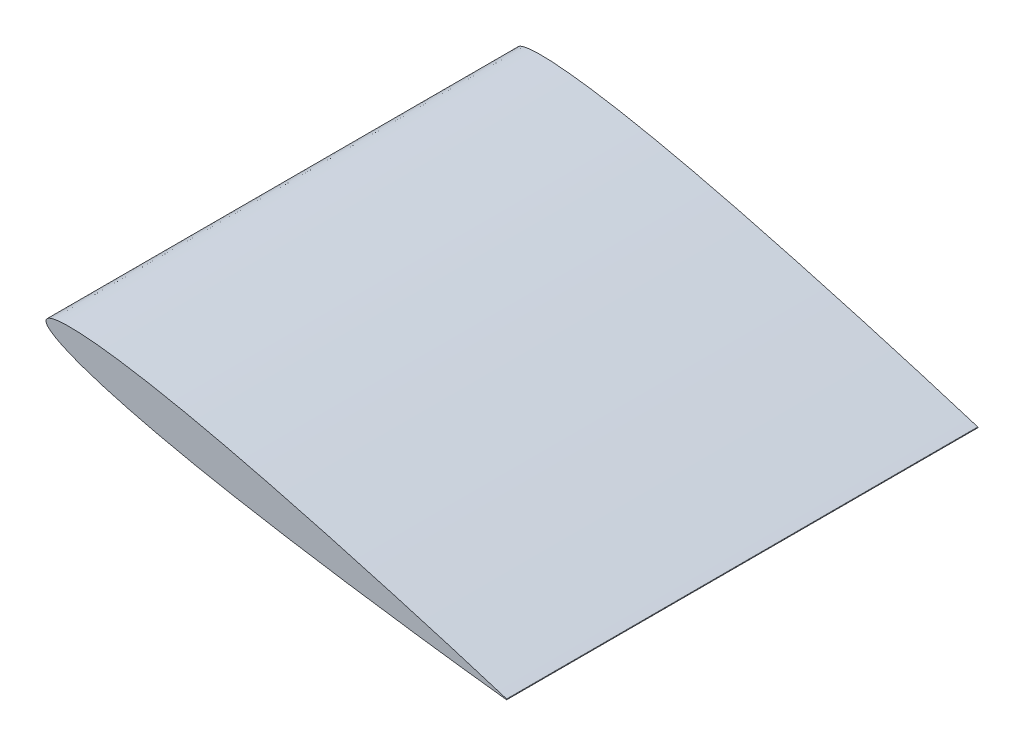
SolidWorks part; units mm, degrees
ref_plane "Front Plane"
ref_plane "Top Plane" through (0, 0, 0) normal (0, 1, 0) x (1, 0, 0)
ref_plane "Right Plane" through (0, 0, 0) normal (1, 0, 0) x (0, 0, -1)
curve "Curve1"
  spline degree 3 poles (25.4, 0.0213, 0) (25.3979, 0.0215, 0) (25.3896, 0.0223, 0) (25.3708, 0.0241, 0) (25.3395, 0.027, 0) (25.2957, 0.0311, 0) (25.2395, 0.0363, 0) (25.1709, 0.0426, 0) (25.0901, 0.0501, 0) (24.997, 0.0587, 0) (24.8917, 0.0683, 0) (24.7744, 0.079, 0) (24.6452, 0.0907, 0) (24.5043, 0.1034, 0) (24.3517, 0.117, 0) (24.1875, 0.1315, 0) (24.0121, 0.147, 0) (23.8254, 0.1632, 0) (23.6278, 0.1803, 0) (23.4194, 0.1981, 0) (23.2005, 0.2167, 0) (22.9711, 0.2359, 0) (22.7317, 0.2558, 0) (22.4823, 0.2763, 0) (22.2233, 0.2973, 0) (21.9549, 0.3188, 0) (21.6773, 0.3408, 0) (21.3909, 0.3631, 0) (21.0959, 0.3859, 0) (20.7926, 0.4089, 0) (20.4814, 0.4323, 0) (20.1624, 0.4558, 0) (19.8361, 0.4795, 0) (19.5028, 0.5034, 0) (19.1627, 0.5274, 0) (18.8163, 0.5513, 0) (18.4638, 0.5753, 0) (18.1056, 0.5992, 0) (17.7421, 0.6229, 0) (17.3737, 0.6466, 0) (17.0006, 0.6699, 0) (16.6232, 0.693, 0) (16.242, 0.7158, 0) (15.8573, 0.7382, 0) (15.4695, 0.7601, 0) (15.079, 0.7816, 0) (14.6861, 0.8025, 0) (14.2912, 0.8228, 0) (13.8948, 0.8424, 0) (13.4972, 0.8613, 0) (13.0988, 0.8794, 0) (12.7, 0.8966, 0) (12.3012, 0.9129, 0) (11.9028, 0.9283, 0) (11.5052, 0.9426, 0) (11.1088, 0.9558, 0) (10.7139, 0.9679, 0) (10.3211, 0.9787, 0) (9.9305, 0.9884, 0) (9.5427, 0.9966, 0) (9.158, 1.0035, 0) (8.7768, 1.009, 0) (8.3995, 1.0131, 0) (8.0264, 1.0156, 0) (7.6579, 1.0165, 0) (7.2944, 1.016, 0) (6.9362, 1.0137, 0) (6.5837, 1.0099, 0) (6.2373, 1.0044, 0) (5.8972, 0.9972, 0) (5.5639, 0.9883, 0) (5.2375, 0.9777, 0) (4.9186, 0.9655, 0) (4.6073, 0.9514, 0) (4.304, 0.9358, 0) (4.009, 0.9184, 0) (3.7226, 0.8995, 0) (3.4451, 0.8788, 0) (3.1766, 0.8566, 0) (2.9176, 0.8328, 0) (2.6682, 0.8075, 0) (2.4287, 0.7806, 0) (2.1994, 0.7523, 0) (1.9804, 0.7226, 0) (1.7719, 0.6915, 0) (1.5743, 0.6591, 0) (1.3876, 0.6255, 0) (1.2121, 0.5906, 0) (1.0479, 0.5546, 0) (0.8952, 0.5175, 0) (0.7542, 0.4794, 0) (0.6249, 0.4403, 0) (0.5074, 0.4002, 0) (0.402, 0.3593, 0) (0.3086, 0.3175, 0) (0.2274, 0.275, 0) (0.1583, 0.2316, 0) (0.1014, 0.1873, 0) (0.0567, 0.1422, 0) (0.0243, 0.096, 0) (0.0045, 0.0485, 0) (-0.0022, 0, 0) (0.0045, -0.0485, 0) (0.0243, -0.096, 0) (0.0567, -0.1422, 0) (0.1014, -0.1873, 0) (0.1583, -0.2316, 0) (0.2274, -0.275, 0) (0.3086, -0.3175, 0) (0.402, -0.3593, 0) (0.5074, -0.4002, 0) (0.6249, -0.4403, 0) (0.7542, -0.4794, 0) (0.8952, -0.5175, 0) (1.0479, -0.5546, 0) (1.2121, -0.5906, 0) (1.3876, -0.6255, 0) (1.5743, -0.6591, 0) (1.7719, -0.6915, 0) (1.9804, -0.7226, 0) (2.1994, -0.7523, 0) (2.4287, -0.7806, 0) (2.6682, -0.8075, 0) (2.9176, -0.8328, 0) (3.1766, -0.8566, 0) (3.4451, -0.8788, 0) (3.7226, -0.8995, 0) (4.009, -0.9184, 0) (4.304, -0.9358, 0) (4.6073, -0.9514, 0) (4.9186, -0.9655, 0) (5.2375, -0.9777, 0) (5.5639, -0.9883, 0) (5.8972, -0.9972, 0) (6.2373, -1.0044, 0) (6.5837, -1.0099, 0) (6.9362, -1.0137, 0) (7.2944, -1.016, 0) (7.6579, -1.0165, 0) (8.0264, -1.0156, 0) (8.3995, -1.0131, 0) (8.7768, -1.009, 0) (9.158, -1.0035, 0) (9.5427, -0.9966, 0) (9.9305, -0.9884, 0) (10.3211, -0.9787, 0) (10.7139, -0.9679, 0) (11.1088, -0.9558, 0) (11.5052, -0.9426, 0) (11.9028, -0.9283, 0) (12.3012, -0.9129, 0) (12.7, -0.8966, 0) (13.0988, -0.8794, 0) (13.4972, -0.8613, 0) (13.8948, -0.8424, 0) (14.2912, -0.8228, 0) (14.6861, -0.8025, 0) (15.079, -0.7816, 0) (15.4695, -0.7601, 0) (15.8573, -0.7382, 0) (16.242, -0.7158, 0) (16.6232, -0.693, 0) (17.0006, -0.6699, 0) (17.3737, -0.6466, 0) (17.7421, -0.6229, 0) (18.1056, -0.5992, 0) (18.4638, -0.5753, 0) (18.8163, -0.5513, 0) (19.1627, -0.5274, 0) (19.5028, -0.5034, 0) (19.8361, -0.4795, 0) (20.1624, -0.4558, 0) (20.4814, -0.4323, 0) (20.7926, -0.4089, 0) (21.0959, -0.3859, 0) (21.3909, -0.3631, 0) (21.6773, -0.3408, 0) (21.9549, -0.3188, 0) (22.2233, -0.2973, 0) (22.4823, -0.2763, 0) (22.7317, -0.2558, 0) (22.9711, -0.2359, 0) (23.2005, -0.2167, 0) (23.4194, -0.1981, 0) (23.6278, -0.1803, 0) (23.8254, -0.1632, 0) (24.0121, -0.147, 0) (24.1875, -0.1315, 0) (24.3517, -0.117, 0) (24.5043, -0.1034, 0) (24.6452, -0.0907, 0) (24.7744, -0.079, 0) (24.8917, -0.0683, 0) (24.997, -0.0587, 0) (25.0901, -0.0501, 0) (25.1709, -0.0426, 0) (25.2395, -0.0363, 0) (25.2957, -0.0311, 0) (25.3395, -0.027, 0) (25.3708, -0.0241, 0) (25.3896, -0.0223, 0) (25.3979, -0.0215, 0) (25.4, -0.0213, 0) knots 0 0 0 0 0.000123 0.000491 0.001103 0.00196 0.003061 0.004403 0.005987 0.00781 0.00987 0.012166 0.014695 0.017455 0.020443 0.023655 0.027089 0.030742 0.034609 0.038686 0.042971 0.047458 0.052143 0.057021 0.062088 0.067338 0.072766 0.078367 0.084136 0.090066 0.096151 0.102387 0.108765 0.115282 0.121928 0.128698 0.135587 0.142585 0.149687 0.156886 0.164174 0.171545 0.17899 0.186504 0.194077 0.201703 0.209374 0.217082 0.224821 0.232582 0.240357 0.248139 0.255921 0.263694 0.271451 0.279184 0.286886 0.29455 0.302166 0.309729 0.317231 0.324663 0.332021 0.339295 0.346479 0.353566 0.360549 0.367422 0.374177 0.380809 0.387311 0.393676 0.399899 0.405973 0.411894 0.417656 0.423252 0.428678 0.43393 0.439001 0.443888 0.448586 0.453092 0.4574 0.461508 0.465412 0.46911 0.472598 0.475875 0.478937 0.481785 0.484418 0.486835 0.489038 0.491029 0.492814 0.494398 0.495793 0.497018 0.498099 0.499075 0.5 0.500925 0.501901 0.502982 0.504207 0.505602 0.507186 0.508971 0.510962 0.513165 0.515582 0.518215 0.521063 0.524125 0.527402 0.53089 0.534588 0.538492 0.5426 0.546908 0.551414 0.556112 0.560999 0.56607 0.571322 0.576748 0.582344 0.588106 0.594027 0.600101 0.606324 0.612689 0.619191 0.625823 0.632578 0.639451 0.646434 0.653521 0.660705 0.667979 0.675337 0.682769 0.690271 0.697834 0.70545 0.713114 0.720816 0.728549 0.736306 0.744079 0.751861 0.759643 0.767418 0.775179 0.782918 0.790626 0.798297 0.805923 0.813496 0.82101 0.828455 0.835826 0.843114 0.850313 0.857415 0.864413 0.871302 0.878072 0.884718 0.891235 0.897613 0.903849 0.909934 0.915864 0.921633 0.927234 0.932662 0.937912 0.942979 0.947857 0.952542 0.957029 0.961314 0.965391 0.969258 0.972911 0.976345 0.979557 0.982545 0.985305 0.987834 0.99013 0.99219 0.994013 0.995597 0.996939 0.99804 0.998897 0.999509 0.999877 1 1 1 1
sketch "Sketch1" plane through (0, 0, 0) normal (0, 0, 1) x (1, 0, 0)
  line L0 (-46.5843, 9.9018) -> (139.7528, -29.7054) construction
  line L1 (-46.5843, 9.9018) -> (-43.564, 24.1112) construction
  line L2 (137.9956, -41.6002) -> (-52.5044, -41.6002) construction
  arc A0 (139.6437, -29.5186) -> (139.577, -29.8314) centre (139.5958, -29.6719) cw
  spline S1 degree 3 poles (139.6437, -29.5186) (139.4038, -29.4437) (139.0294, -29.3265) (138.4907, -29.1583) (137.998, -29.0047) (137.4169, -28.8236) (136.7477, -28.6156) (135.9915, -28.3804) (135.1484, -28.1191) (134.2197, -27.8318) (133.2063, -27.5184) (132.1088, -27.1804) (130.9285, -26.8174) (129.6665, -26.4302) (128.3239, -26.0194) (126.9022, -25.5858) (125.4026, -25.1294) (123.8266, -24.6514) (122.1756, -24.1524) (120.4515, -23.6326) (118.6556, -23.0932) (116.7898, -22.5348) (114.8559, -21.9576) (112.8558, -21.3632) (110.7913, -20.752) (108.6647, -20.1245) (106.4777, -19.4819) (104.2327, -18.8247) (101.9317, -18.1538) (99.5769, -17.4705) (97.1708, -16.7748) (94.7156, -16.0682) (92.2136, -15.3515) (89.6675, -14.6252) (87.0795, -13.891) (84.4522, -13.1491) (81.7882, -12.4004) (79.0899, -11.6466) (76.3603, -10.8878) (73.6017, -10.1255) (70.817, -9.3605) (67.06, -8.3352) (63.2765, -7.3123) (59.4696, -6.2948) (56.5946, -5.5316) (53.7096, -4.7724) (50.8177, -4.0177) (47.9216, -3.2683) (45.0241, -2.5261) (42.1279, -1.7914) (39.2359, -1.0653) (36.3507, -0.3494) (33.4753, 0.3559) (30.6124, 1.0489) (27.7647, 1.7295) (24.9349, 2.3955) (22.1261, 3.0473) (19.3404, 3.6825) (16.581, 4.3017) (13.8501, 4.9026) (10.2759, 5.6742) (6.7471, 6.4123) (3.2669, 7.114) (0.719, 7.6146) (-1.7849, 8.093) (-4.2422, 8.5488) (-6.6507, 8.9806) (-9.0076, 9.389) (-11.3111, 9.7724) (-13.5585, 10.1314) (-15.7479, 10.465) (-17.877, 10.7732) (-20.5878, 11.1433) (-23.2128, 11.4687) (-25.7495, 11.7455) (-27.5468, 11.9224) (-29.2721, 12.0735) (-30.9237, 12.1975) (-32.4999, 12.2954) (-33.9992, 12.3667) (-35.42, 12.4116) (-36.7609, 12.4304) (-38.0206, 12.4228) (-39.1977, 12.3894) (-40.2913, 12.3305) (-41.3002, 12.2456) (-42.2235, 12.1354) (-43.0604, 12.0003) (-43.81, 11.8396) (-44.4721, 11.6545) (-45.0462, 11.4442) (-45.5323, 11.209) (-45.9305, 10.9482) (-46.2402, 10.6599) (-46.4597, 10.3425) (-46.5839, 9.9975) (-46.6111, 9.6318) (-46.54, 9.2526) (-46.3748, 8.8631) (-46.1174, 8.4626) (-45.7695, 8.0497) (-45.331, 7.6236) (-44.8018, 7.1847) (-44.1828, 6.7324) (-43.4737, 6.2679) (-42.6755, 5.7909) (-41.7889, 5.302) (-40.8143, 4.8025) (-39.753, 4.2922) (-38.6058, 3.7718) (-37.3737, 3.2423) (-36.058, 2.7042) (-34.6599, 2.1581) (-33.1807, 1.605) (-31.622, 1.0449) (-29.9849, 0.4796) (-28.2716, -0.0915) (-25.8425, -0.8728) (-23.3127, -1.6457) (-20.6865, -2.4127) (-18.6167, -2.9992) (-16.4815, -3.587) (-14.2829, -4.1754) (-12.0233, -4.7642) (-9.7045, -5.3521) (-7.3292, -5.9395) (-4.8996, -6.525) (-2.4182, -7.1089) (0.1126, -7.6903) (3.5765, -8.4683) (7.0997, -9.2327) (10.678, -9.9851) (13.4166, -10.5496) (16.1887, -11.109) (18.9914, -11.6645) (21.822, -12.2144) (24.6775, -12.7597) (27.5552, -13.299) (30.4521, -13.8332) (33.3652, -14.3613) (36.2916, -14.8837) (39.2284, -15.3995) (42.1725, -15.9093) (45.121, -16.4126) (48.0709, -16.9089) (51.0193, -17.3986) (53.9632, -17.8813) (56.8996, -18.3563) (60.7907, -18.9791) (64.6625, -19.5873) (68.5111, -20.1825) (71.3659, -20.6191) (74.1956, -21.0475) (76.9974, -21.4674) (79.7686, -21.8789) (82.5064, -22.2812) (85.2079, -22.6747) (87.8705, -23.0592) (90.4915, -23.4339) (93.0683, -23.7993) (95.5983, -24.1549) (98.079, -24.5005) (100.5078, -24.8364) (102.8824, -25.1617) (105.2004, -25.4768) (107.4593, -25.7815) (109.6571, -26.0754) (111.7914, -26.3588) (113.8601, -26.6313) (115.8612, -26.8926) (117.7927, -27.1433) (119.6524, -27.3828) (121.4387, -27.6109) (123.1496, -27.8283) (124.7837, -28.0342) (126.339, -28.2288) (127.8141, -28.4124) (129.2075, -28.5845) (130.5177, -28.7454) (131.7434, -28.895) (132.8834, -29.0338) (133.9365, -29.1607) (134.9017, -29.277) (135.778, -29.3821) (136.5645, -29.4756) (137.2603, -29.5583) (137.8648, -29.6299) (138.5644, -29.7126) (139.1249, -29.7783) (139.5145, -29.8241) (139.577, -29.8314) knots 0 0 0 0 0.00196 0.003061 0.004403 0.005987 0.00781 0.00987 0.012166 0.014695 0.017455 0.020443 0.023655 0.027089 0.030742 0.034609 0.038686 0.042971 0.047458 0.052143 0.057021 0.062088 0.067338 0.072766 0.078367 0.084136 0.090066 0.096151 0.102387 0.108765 0.115282 0.121928 0.128698 0.135587 0.142585 0.149687 0.156886 0.164174 0.171545 0.17899 0.186504 0.194077 0.209374 0.217082 0.224821 0.232582 0.240357 0.248139 0.255921 0.263694 0.271451 0.279184 0.286886 0.29455 0.302166 0.309729 0.317231 0.324663 0.332021 0.339295 0.346479 0.360549 0.367422 0.374177 0.380809 0.387311 0.393676 0.399899 0.405973 0.411894 0.417656 0.423252 0.428678 0.439001 0.443888 0.448586 0.453092 0.4574 0.461508 0.465412 0.46911 0.472598 0.475875 0.478937 0.481785 0.484418 0.486835 0.489038 0.491029 0.492814 0.494398 0.495793 0.497018 0.498099 0.499075 0.5 0.500925 0.501901 0.502982 0.504207 0.505602 0.507186 0.508971 0.510962 0.513165 0.515582 0.518215 0.521063 0.524125 0.527402 0.53089 0.534588 0.538492 0.5426 0.546908 0.551414 0.556112 0.560999 0.571322 0.576748 0.582344 0.588106 0.594027 0.600101 0.606324 0.612689 0.619191 0.625823 0.632578 0.639451 0.653521 0.660705 0.667979 0.675337 0.682769 0.690271 0.697834 0.70545 0.713114 0.720816 0.728549 0.736306 0.744079 0.751861 0.759643 0.767418 0.775179 0.782918 0.790626 0.805923 0.813496 0.82101 0.828455 0.835826 0.843114 0.850313 0.857415 0.864413 0.871302 0.878072 0.884718 0.891235 0.897613 0.903849 0.909934 0.915864 0.921633 0.927234 0.932662 0.937912 0.942979 0.947857 0.952542 0.957029 0.961314 0.965391 0.969258 0.972911 0.976345 0.979557 0.982545 0.985305 0.987834 0.99013 0.99219 0.994013 0.995597 0.996939 0.999509 1 1 1 1
  point P7 (0, 0)
  dimension "D1" = 190.5
  dimension "D2" = 47.625
  dimension "D3" = 12
extrude "Boss-Extrude1" add sketch "Sketch1" against normal blind 190.5
